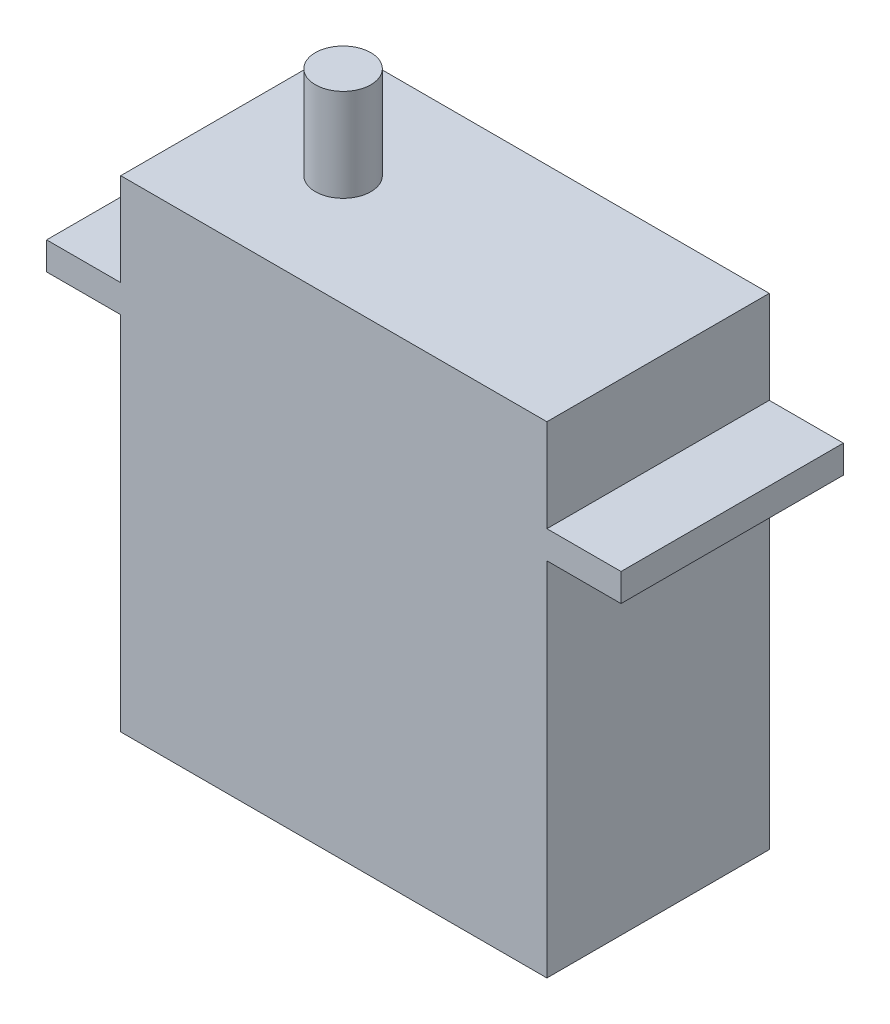
SolidWorks part; units mm, degrees
ref_plane "Front Plane" through (0, 0, 0) normal (0, 0, 1) x (1, 0, 0)
ref_plane "Top Plane" through (0, 0, 0) normal (0, 1, 0) x (1, 0, 0)
ref_plane "Right Plane" through (0, 0, 0) normal (1, 0, 0) x (0, 0, -1)
sketch "Sketch1" plane through (0, 0, 0) normal (0, 1, 0) x (1, 0, 0)
  line L1 (-11.5, 6) -> (11.5, 6)
  line L2 (-11.5, 6) -> (-11.5, -6)
  line L3 (-11.5, -6) -> (11.5, -6)
  line L4 (11.5, 6) -> (11.5, -6)
  line L5 (-11.5, 6) -> (11.5, -6) construction
  line L6 (-11.5, -6) -> (11.5, 6) construction
  point P0 (0, 0)
  dimension "D1" = 23
  dimension "D2" = 12
extrude "Boss-Extrude1" add sketch "Sketch1" along normal blind 26
sketch "Sketch2" plane through (11.5, 0, 0) normal (1, 0, 0) x (0, 0, -1)
  line L0 (-6, 26) -> (-6, 0) construction
  line L1 (-6, 21) -> (6, 21)
  line L2 (-6, 21) -> (-6, 19.5)
  line L3 (-6, 19.5) -> (6, 19.5)
  line L4 (6, 21) -> (6, 19.5)
  line L5 (6, 26) -> (6, 0) construction
  line L6 (-6, 0) -> (6, 0) construction
  dimension "D1" = 19.5
  dimension "D2" = 1.5
extrude "Boss-Extrude2" add sketch "Sketch2" along normal blind 4
mirror "Mirror1" about plane through (0, 0, 0) normal (1, 0, 0) of "Boss-Extrude2"
sketch "Sketch3" plane through (0, 26, 0) normal (0, 1, 0) x (1, 0, 0)
  line L0 (-11.5, 6) -> (-11.5, -6) construction
  line L1 (-11.5, 6) -> (-11.5, -6) construction
  circle A0 centre (-5.5, 0) radius 1.5
  point P4 (0, 0)
  point P7 (-11.5, 0)
  dimension "D1" = 3
  dimension "D2" = 6
extrude "Boss-Extrude3" add sketch "Sketch3" along normal blind 5
